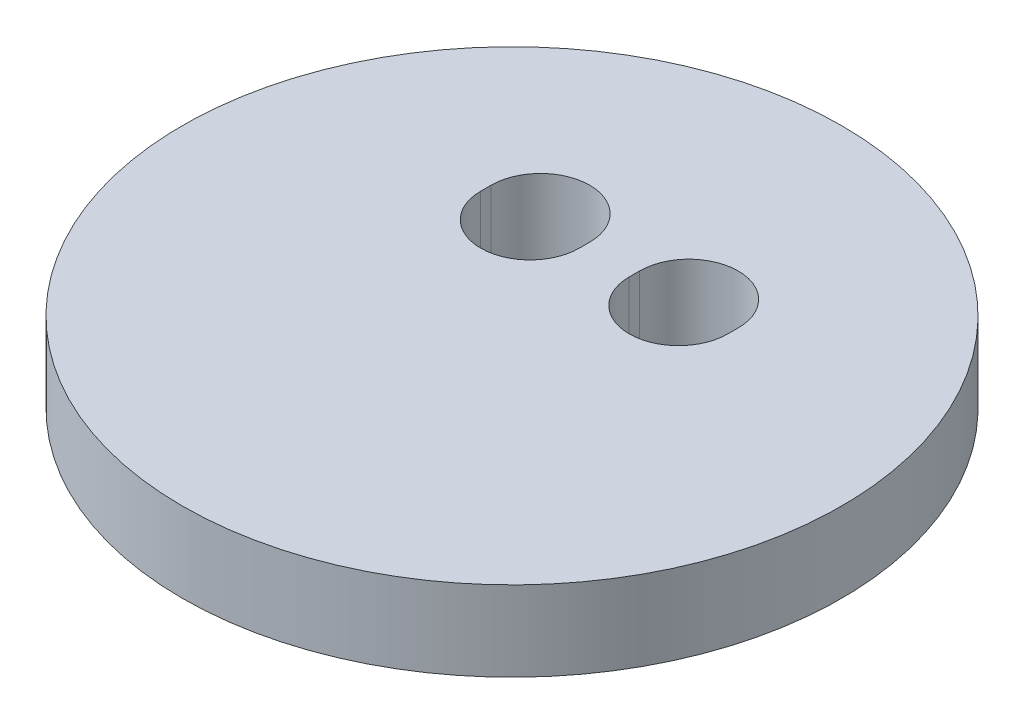
SolidWorks part; units mm, degrees
ref_plane "Front Plane" through (0, 0, 0) normal (0, 0, 1) x (1, 0, 0)
ref_plane "Top Plane" through (0, 0, 0) normal (0, 1, 0) x (1, 0, 0)
ref_plane "Right Plane" through (0, 0, 0) normal (1, 0, 0) x (0, 0, -1)
sketch "Sketch1" plane through (0, 0, 0) normal (0, 1, 0) x (1, 0, 0)
  circle A0 centre (0, 0) radius 12.36
  point P3 (0, 0)
  dimension "D1" = 24.72
extrude "Boss-Extrude1" add sketch "Sketch1" along normal blind 3
sketch "Sketch2" plane through (0, 3, 0) normal (0, 1, 0) x (1, 0, 0)
  line L0 (-2.785, 3.85) -> (-2.785, 3.46) construction
  line L1 (2.785, 3.85) -> (2.785, 3.46) construction
  line L2 (4.635, 3.85) -> (4.635, 3.46)
  line L3 (0.935, 3.85) -> (0.935, 3.46)
  line L4 (-0.935, 3.85) -> (-0.935, 3.46)
  line L5 (-4.635, 3.85) -> (-4.635, 3.46)
  line L6 (-2.785, 5.7) -> (2.785, 5.7) construction
  arc A3 (4.635, 3.85) -> (0.935, 3.85) centre (2.785, 3.85) ccw
  arc A4 (0.935, 3.46) -> (4.635, 3.46) centre (2.785, 3.46) ccw
  arc A5 (-0.935, 3.85) -> (-4.635, 3.85) centre (-2.785, 3.85) ccw
  arc A6 (-4.635, 3.46) -> (-0.935, 3.46) centre (-2.785, 3.46) ccw
  circle A7 centre (0, 0) radius 12.36 construction
  point P1 (-2.785, 3.655)
  point P2 (-4.635, 3.655)
  point P3 (-0.935, 3.655)
  point P8 (2.785, 3.655)
  point P14 (2.785, 5.7)
  point P15 (2.785, 1.61)
  point P16 (4.635, 3.655)
  point P17 (0.935, 3.655)
  point P20 (-2.785, 5.7)
  point P24 (-2.785, 1.61)
  point P29 (0, 5.7)
  dimension "D2" = 4.09
  dimension "D1" = 3.7
  dimension "D3" = 3.7
  dimension "D4" = 4.09
  dimension "D5" = 5.7
  dimension "D6" = 5.57
extrude "Cut-Extrude1" cut sketch "Sketch2" against normal through all
